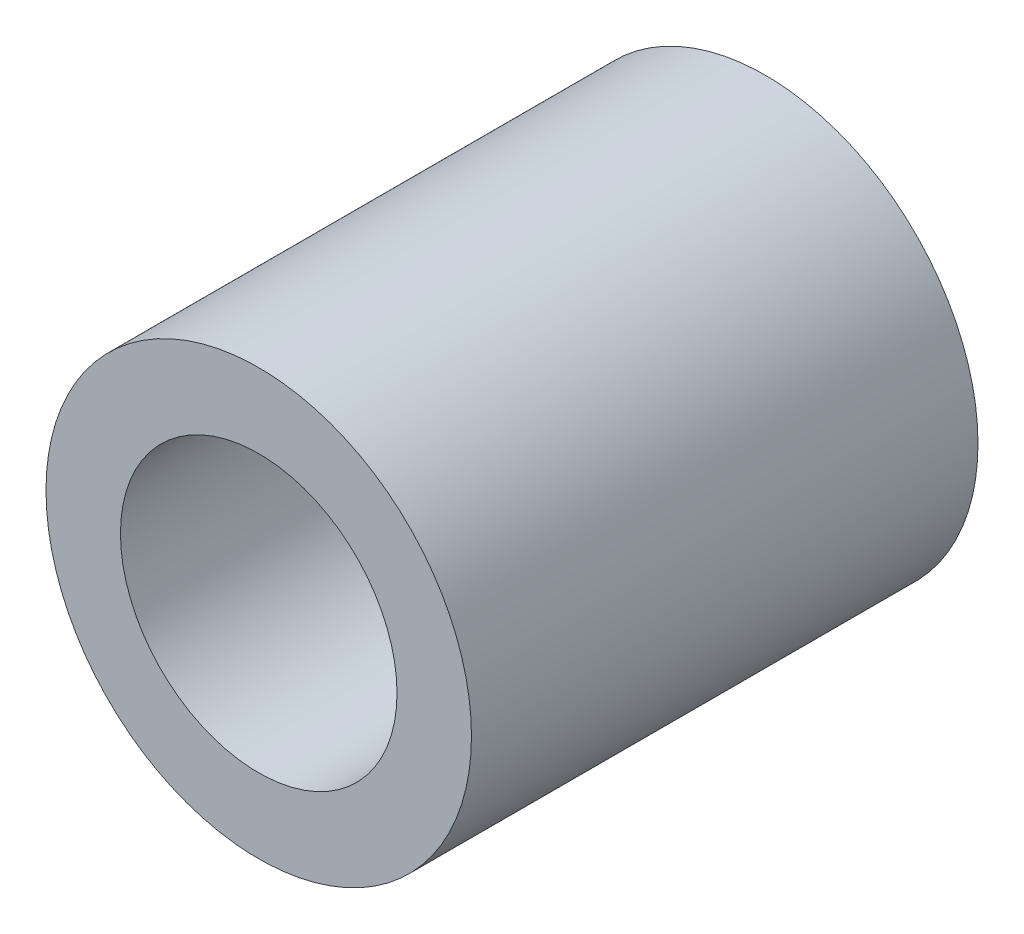
SolidWorks part; units mm, degrees
material "PVC Rigid"
ref_plane "Front" through (0, 0, 0) normal (0, 0, 1) x (1, 0, 0)
ref_plane "Top" through (0, 0, 0) normal (0, 1, 0) x (1, 0, 0)
ref_plane "Right" through (0, 0, 0) normal (1, 0, 0) x (0, 0, -1)
sketch "Sketch1" plane through (0, 0, 0) normal (0, 0, 1) x (1, 0, 0)
  circle A0 centre (0, 0) radius 6.9342
  circle A1 centre (0, 0) radius 10.668
  dimension "D1" = 21.336
  dimension "D2" = 13.8684
extrude "Boss-Extrude1" add sketch "Sketch1" along normal blind 25.4
